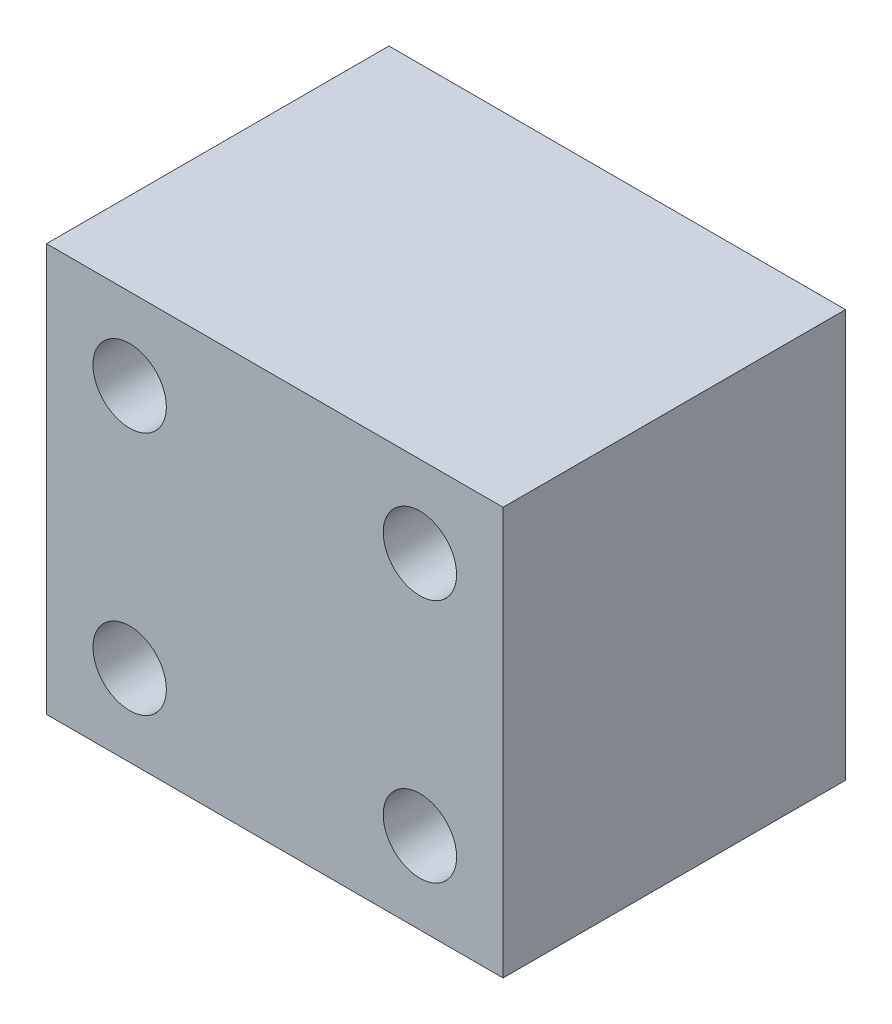
SolidWorks part; units mm, degrees
ref_plane "前视基准面" through (0, 0, 0) normal (0, 0, 1) x (1, 0, 0)
ref_plane "上视基准面" through (0, 0, 0) normal (0, 1, 0) x (1, 0, 0)
ref_plane "右视基准面" through (0, 0, 0) normal (1, 0, 0) x (0, 0, -1)
sketch "草图1" plane through (0, 0, 0) normal (0, 0, 1) x (1, 0, 0)
  line L1 (-14, 12.5) -> (14, 12.5)
  line L2 (-14, 12.5) -> (-14, -12.5)
  line L3 (-14, -12.5) -> (14, -12.5)
  line L4 (14, 12.5) -> (14, -12.5)
  line L5 (0, -12.5) -> (0, 12.5) construction
  line L6 (-14, 0) -> (14, 0) construction
  point P0 (0, 0)
  dimension "D1" = 28
  dimension "D2" = 25
extrude "凸台-拉伸1" add sketch "草图1" along normal blind 21
sketch "草图2" plane through (0, 0, 21) normal (0, 0, 1) x (1, 0, 0)
  circle A0 centre (-8.9, -7.5) radius 2.25
  circle A1 centre (8.9, -7.5) radius 2.25
  circle A2 centre (8.9, 7.5) radius 2.25
  circle A3 centre (-8.9, 7.5) radius 2.25
  point P8 (0, 0)
  point P10 (0, 0)
  dimension "D5" = 4.5
  dimension "D1" = 15
  dimension "D2" = 17.8
  dimension "D3" = 8.9
  dimension "D4" = 7.5
extrude "切除-拉伸1" cut sketch "草图2" against normal blind 21
